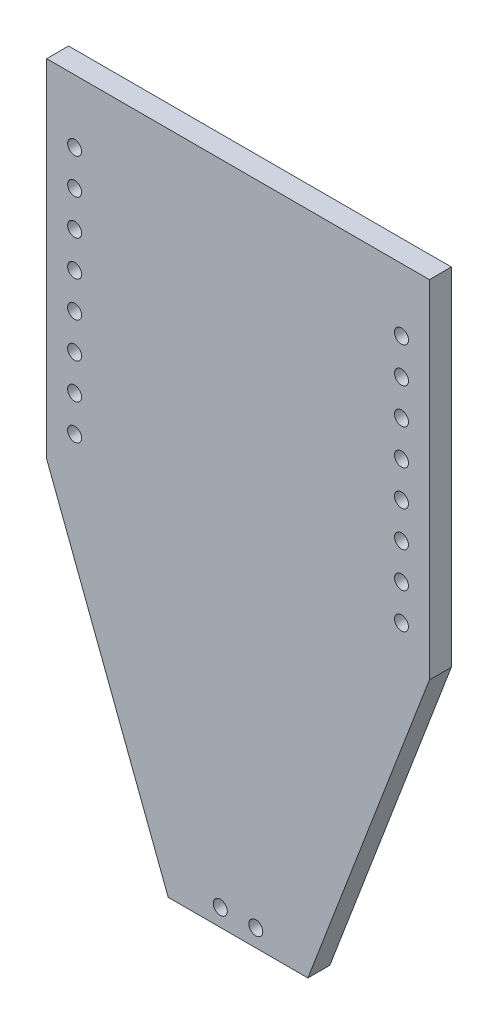
SolidWorks part; units mm, degrees
ref_plane "Front Plane" through (0, 0, 0) normal (0, 0, 1) x (1, 0, 0)
ref_plane "Top Plane" through (0, 0, 0) normal (0, 1, 0) x (1, 0, 0)
ref_plane "Right Plane" through (0, 0, 0) normal (1, 0, 0) x (0, 0, -1)
sketch "Sketch1" plane through (0, 0, 0) normal (0, 0, 1) x (1, 0, 0)
  line L0 (0, 19.85) -> (0, -19.85)
  line L1 (13.7, -19.85) -> (-13.7, -19.85)
  line L2 (13.7, -19.85) -> (13.7, 19.85)
  line L3 (13.7, 19.85) -> (-13.7, 19.85)
  line L4 (-13.7, -19.85) -> (-13.7, 19.85)
  line L5 (13.7, -19.85) -> (-13.7, 19.85) construction
  line L6 (13.7, 19.85) -> (-13.7, -19.85) construction
  line L7 (-13.7, -4.97) -> (-5, -27.8)
  line L8 (-5, -19.85) -> (5, -19.85)
  line L9 (-5, -19.85) -> (-5, -27.8)
  line L10 (-5, -27.8) -> (5, -27.8)
  line L11 (5, -19.85) -> (5, -27.8)
  line L12 (5, -27.8) -> (13.7, -4.97)
  circle A0 centre (-11.7, 15.35) radius 0.5
  circle A1 centre (-11.7, 12.81) radius 0.5
  circle A2 centre (-11.7, 10.27) radius 0.5
  circle A3 centre (-11.7, 7.73) radius 0.5
  circle A4 centre (-11.7, 5.19) radius 0.5
  circle A5 centre (-11.7, 2.65) radius 0.5
  circle A6 centre (-11.7, 0.11) radius 0.5
  circle A7 centre (-11.7, -2.43) radius 0.5
  circle A8 centre (11.7, -2.43) radius 0.5
  circle A9 centre (11.7, 0.11) radius 0.5
  circle A10 centre (11.7, 2.65) radius 0.5
  circle A11 centre (11.7, 5.19) radius 0.5
  circle A12 centre (11.7, 7.73) radius 0.5
  circle A13 centre (11.7, 10.27) radius 0.5
  circle A14 centre (11.7, 12.81) radius 0.5
  circle A15 centre (11.7, 15.35) radius 0.5
  circle A16 centre (-1.27, -26.55) radius 0.5
  circle A17 centre (1.27, -26.55) radius 0.5
  point P0 (0, 0)
  dimension "D3" = 1
  dimension "D4" = 4.5
  dimension "D5" = 2
  dimension "D6" = 8
  dimension "D12" = 1
  dimension "D13" = 1
  dimension "D14" = 2.54
  dimension "D16" = 1.25
  dimension "D1" = 27.4
  dimension "D2" = 39.7
  dimension "D7" = 7.95
  dimension "D8" = 10
  dimension "D9" = 5
  dimension "D10" = 2.54
  dimension "D11" = 2.54
  dimension "D15" = 1.27
extrude "Boss-Extrude1" add sketch "Sketch1" along normal blind 1.57 contours L4 L1 L0 L3 A7 A6 A5 A4 A3 A2 A1 A0 | L2 L3 L0 L1 A14 A12 A10 A8 A9 A11 A13 A15 | L11 L12 L1 | L11 L1 L9 L10 A17 A16 | L9 L1 L7
